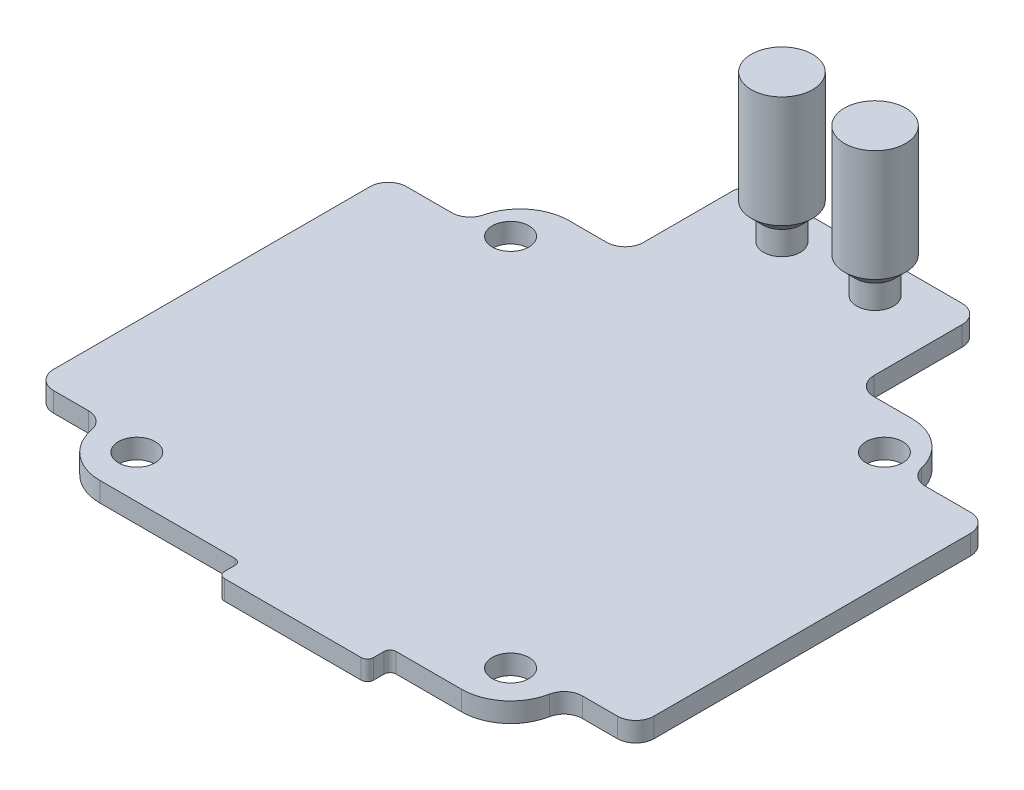
SolidWorks part; units mm, degrees
ref_plane "Front Plane" through (0, 0, 0) normal (0, 0, 1) x (1, 0, 0)
ref_plane "Top Plane" through (0, 0, 0) normal (0, 1, 0) x (1, 0, 0)
ref_plane "Right Plane" through (0, 0, 0) normal (1, 0, 0) x (0, 0, -1)
sketch "Sketch1" plane through (0, 0, 0) normal (0, 1, 0) x (1, 0, 0)
  line L0 (10.9063, 8.4671) -> (41.4062, 8.3877) construction
  line L5 (28.1829, 3.5708) -> (28.1829, 53.1141) construction
  line L6 (12.9329, 8.9243) -> (43.4329, 8.9243)
  line L7 (3.6829, 9.8844) -> (9.4329, 9.8844)
  line L8 (9.4329, 9.8844) -> (9.4329, 5.4243)
  line L9 (9.4329, 5.4243) -> (24.9371, 5.4243)
  line L10 (24.9371, 5.4243) -> (24.9371, 3.5708)
  line L11 (24.9371, 3.5708) -> (37.1009, 3.5708)
  line L12 (37.1009, 3.5708) -> (37.1009, 5.4243)
  line L13 (37.1009, 5.4243) -> (46.9329, 5.4243)
  line L14 (46.9329, 5.4243) -> (46.9329, 9.8844)
  line L15 (46.9329, 9.8844) -> (52.6829, 9.8844)
  line L16 (3.6829, 38.6951) -> (10.2045, 38.6951)
  line L17 (10.2045, 38.6951) -> (10.2045, 42.9243)
  line L18 (10.2045, 42.9243) -> (18.7803, 42.9243)
  line L19 (18.7803, 42.9243) -> (18.7803, 53.1141)
  line L20 (18.7803, 53.1141) -> (37.5855, 53.1141)
  line L21 (3.6829, 38.6951) -> (3.6829, 9.8844)
  line L22 (52.6829, 38.6951) -> (52.6829, 9.8844)
  line L23 (52.6829, 38.6951) -> (46.1613, 38.6951)
  line L24 (46.1613, 38.6951) -> (46.1613, 42.9243)
  line L25 (46.1613, 42.9243) -> (37.5855, 42.9243)
  line L26 (37.5855, 42.9243) -> (37.5855, 53.1141)
  circle A0 centre (12.9329, 8.9243) radius 1.5
  circle A1 centre (43.4329, 8.9243) radius 1.5
  circle A2 centre (43.4329, 39.4243) radius 1.5
  circle A3 centre (12.9329, 39.4243) radius 1.5
  point P12 (28.1829, 8.9243)
  dimension "D4" = 3.5
  dimension "D5" = 3
  dimension "D1" = 30.5
  dimension "D2" = 30.5
  dimension "D3" = 3.6829
  dimension "D7" = 3.5
  dimension "D8" = 15.5042
  dimension "D9" = 12.1638
  dimension "D10" = 4.4601
  dimension "D11" = 1.8535
  dimension "D12" = 9.8844
  dimension "D13" = 24.5
  dimension "D14" = 6.5216
  dimension "D15" = 8.5758
  dimension "D16" = 4.2292
  dimension "D17" = 3.5
  dimension "D18" = 30.5
  dimension "D19" = 10.1898
extrude "Boss-Extrude1" add sketch "Sketch1" along normal blind 1.6
fillet "Fillet1" radius 4 4 edges at (46.1613, 0.8, -42.9243) (10.2045, 0.8, -42.9243) (46.9329, 0.8, -5.4243) (9.4329, 0.8, -5.4243)
fillet "Fillet2" radius 1.5 12 edges at (52.6829, 0.8, -9.8844) (52.6829, 0.8, -38.6951) (37.5855, 0.8, -42.9243) (37.5855, 0.8, -53.1141) (18.7803, 0.8, -53.1141) (18.7803, 0.8, -42.9243) (3.6829, 0.8, -38.6951) (46.9329, 0.8, -9.8844) (9.4329, 0.8, -9.8844) (46.1613, 0.8, -38.6951) (10.2045, 0.8, -38.6951) (3.6829, 0.8, -9.8844)
fillet "Fillet3" radius 0.5 4 edges at (37.1009, 0.8, -3.5708) (37.1009, 0.8, -5.4243) (24.9371, 0.8, -5.4243) (24.9371, 0.8, -3.5708)
sketch "Sketch2" plane through (0, 1.6, 0) normal (0, 1, 0) x (1, 0, 0)
  line L0 (28.1829, 53.1141) -> (28.1829, 44.7636) construction
  line L1 (20.2803, 53.1141) -> (36.0855, 53.1141) construction
  circle A0 centre (31.9829, 50.1141) radius 1.25
  circle A1 centre (24.3829, 50.1141) radius 1.25
  dimension "D4" = 2.5
  dimension "D1" = 8.3505
  dimension "D2" = 3
  dimension "D3" = 7.6
extrude "Boss-Extrude2" add sketch "Sketch2" along normal blind 1.5
sketch "Sketch3" plane through (0, 1.6, 0) normal (0, 1, 0) x (1, 0, 0)
  circle A0 centre (31.9829, 50.1141) radius 1.5
  circle A1 centre (24.3829, 50.1141) radius 1.5
  dimension "D1" = 3
extrude "Boss-Extrude3" add sketch "Sketch3" along normal blind 2
sketch "Sketch4" plane through (0, 3.6, 0) normal (0, 1, 0) x (1, 0, 0)
  circle A0 centre (31.9829, 50.1141) radius 2.5
  circle A1 centre (24.3829, 50.1141) radius 2.5
  dimension "D1" = 5
extrude "Boss-Extrude4" add sketch "Sketch4" along normal blind 10
chamfer "Chamfer1" distance 0.9 angle 45 2 edges at (24.3829, 3.6, -47.6141) (31.9829, 3.6, -47.6141)
